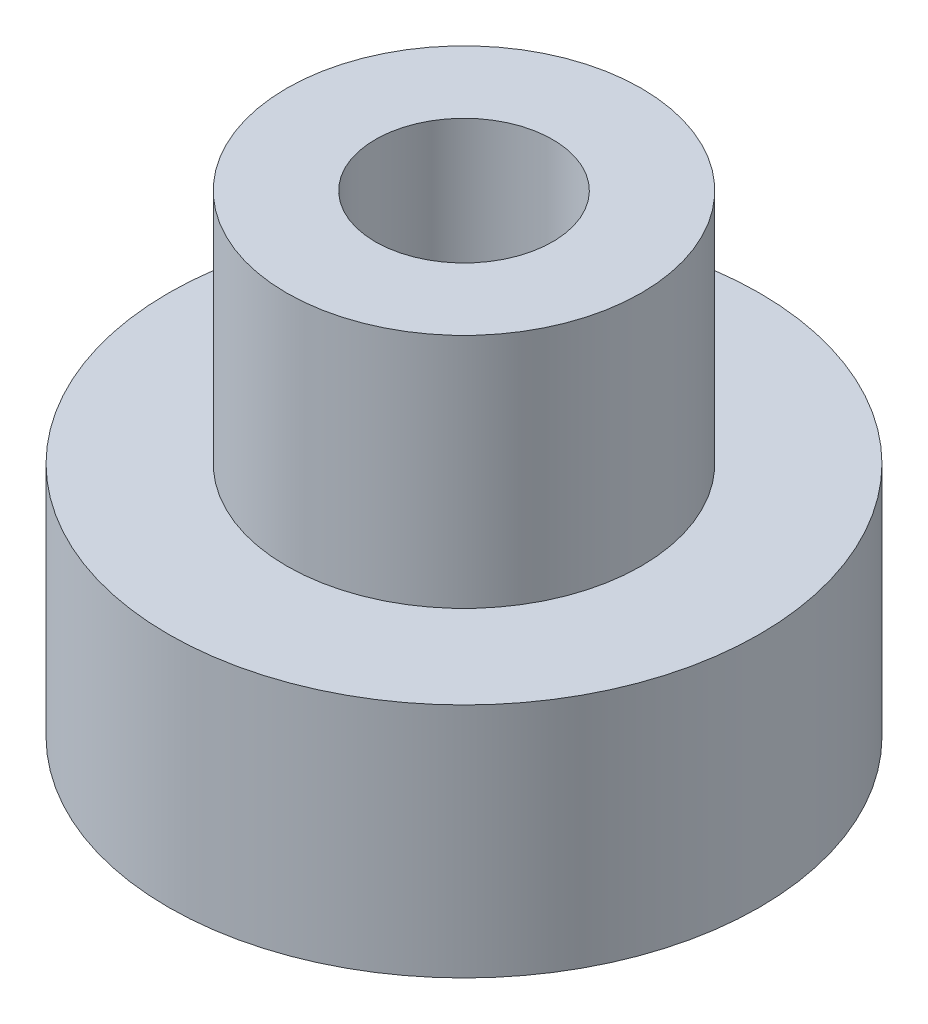
SolidWorks part; units mm, degrees
ref_plane "前视基准面" through (0, 0, 0) normal (0, 0, 1) x (1, 0, 0)
ref_plane "上视基准面" through (0, 0, 0) normal (0, 1, 0) x (1, 0, 0)
ref_plane "右视基准面" through (0, 0, 0) normal (1, 0, 0) x (0, 0, -1)
sketch "草图1" plane through (0, 0, 0) normal (0, 1, 0) x (1, 0, 0)
  circle A0 centre (0, 0) radius 3
  dimension "D1" = 6
extrude "凸台-拉伸1" add sketch "草图1" along normal blind 8
sketch "草图2" plane through (0, 8, 0) normal (0, 1, 0) x (1, 0, 0)
  circle A0 centre (0, 0) radius 1.5
  dimension "D1" = 3
extrude "切除-拉伸1" cut sketch "草图2" against normal blind 8
sketch "草图3" plane through (0, 0, 0) normal (0, -1, 0) x (1, 0, 0)
  circle A0 centre (0, 0) radius 1.5115
  circle A1 centre (0, 0) radius 5
  dimension "D1" = 10
extrude "凸台-拉伸2" add sketch "草图3" against normal blind 4
